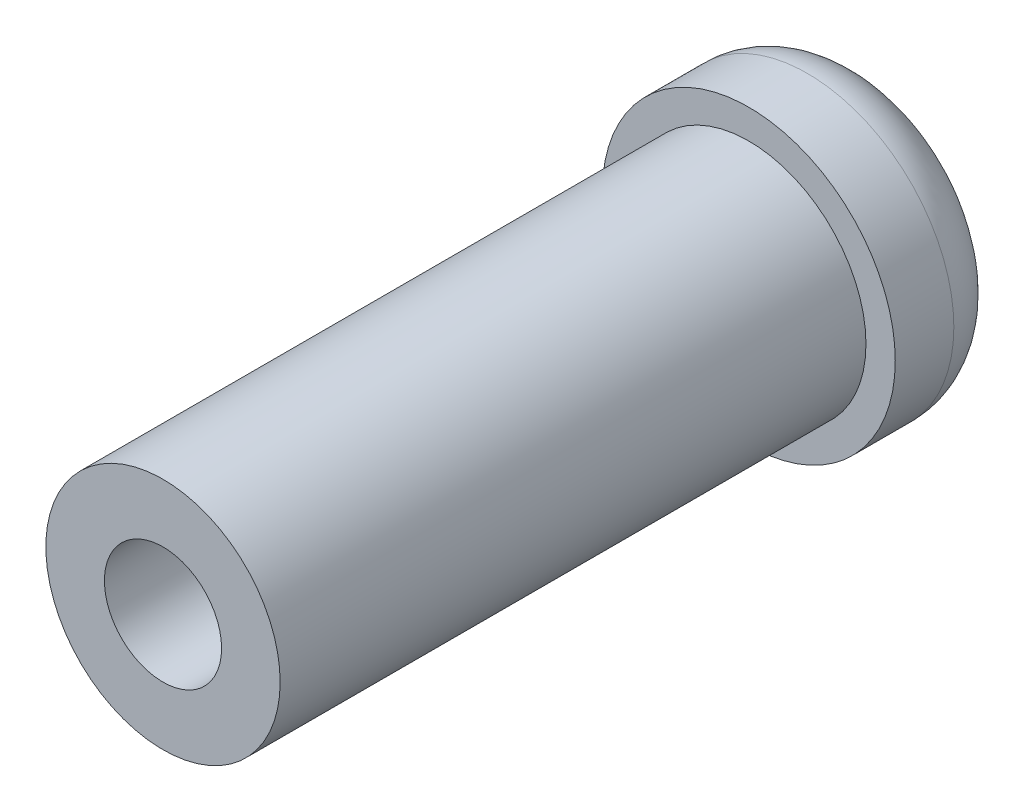
SolidWorks part; units mm, degrees
ref_plane "Plan de face" through (0, 0, 0) normal (0, 0, 1) x (1, 0, 0)
ref_plane "Plan de dessus" through (0, 0, 0) normal (0, 1, 0) x (1, 0, 0)
ref_plane "Plan de droite" through (0, 0, 0) normal (1, 0, 0) x (0, 0, -1)
sketch "Esquisse1" plane through (0, 0, 0) normal (0, 0, 1) x (1, 0, 0)
  circle A0 centre (0, 0) radius 2.5
  dimension "D1" = 5
extrude "Boss.-Extru.1" add sketch "Esquisse1" along normal blind 2
sketch "Esquisse2" plane through (0, 0, 2) normal (0, 0, 1) x (1, 0, 0)
  circle A0 centre (0, 0) radius 2
  circle A1 centre (0, 0) radius 1
  dimension "D1" = 4
  dimension "D2" = 2
extrude "Boss.-Extru.2" add sketch "Esquisse2" along normal blind 10
fillet "Congé1" radius 1 1 edges at (2.5, 0, 0)
